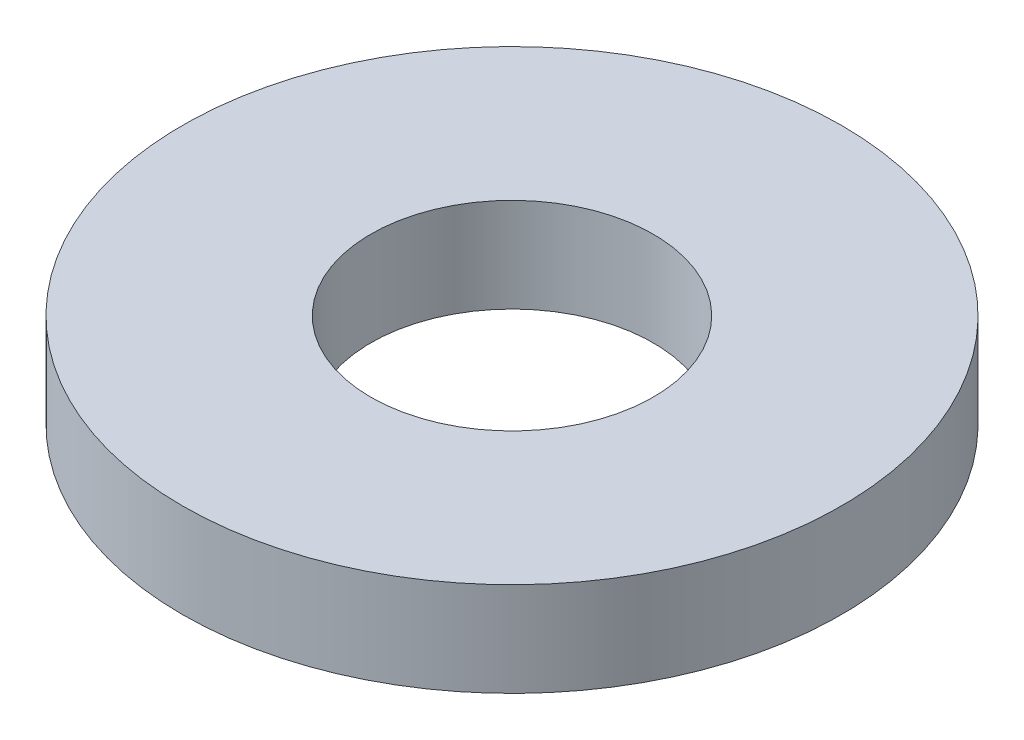
SolidWorks part; units mm, degrees
material "Nylon 6/10"
ref_plane "Front Plane" through (0, 0, 0) normal (0, 0, 1) x (1, 0, 0)
ref_plane "Top Plane" through (0, 0, 0) normal (0, 1, 0) x (1, 0, 0)
ref_plane "Right Plane" through (0, 0, 0) normal (1, 0, 0) x (0, 0, -1)
sketch "Sketch1" plane through (0, 0, 0) normal (0, 1, 0) x (1, 0, 0)
  circle A0 centre (0, 0) radius 2.3813
  circle A1 centre (0, 0) radius 5.5562
  dimension "D1" = 4.7625
  dimension "D2" = 11.1125
extrude "Boss-Extrude1" add sketch "Sketch1" along normal blind 1.5875
